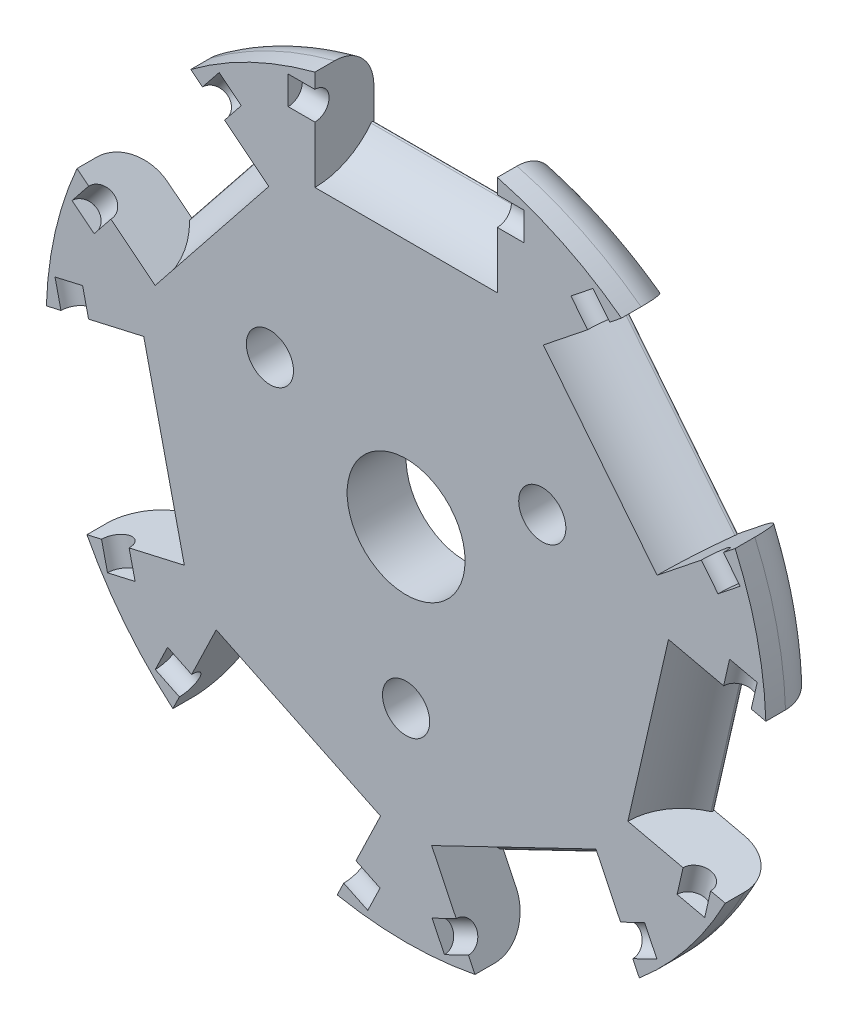
SolidWorks part; units mm, degrees
other "Markup1"
sketch "Sketch8" plane through (32.7336, 32.7336, 0) normal (0.5701, 0.1846, 0.8006) x (0.8043, 0.0736, -0.5897)
ref_plane "Front Plane" through (0, 0, 0) normal (0, 0, 1) x (1, 0, 0)
ref_plane "Top Plane" through (0, 0, 0) normal (0, 1, 0) x (1, 0, 0)
ref_plane "Right Plane" through (0, 0, 0) normal (1, 0, 0) x (0, 0, -1)
sketch "Sketch1" plane through (0, 0, 0) normal (0, 0, 1) x (1, 0, 0)
  circle A0 centre (0, 0) radius 29.0703
  dimension "D1" = 58.1406
extrude "Boss-Extrude2" add sketch "Sketch1" against normal blind 4.7625
fillet "Fillet1" radius 3.175 1 edges at (29.0703, 0, -4.7625)
sketch "Sketch2" plane through (0, 0, 0) normal (0, 0, 1) x (1, 0, 0)
  line L1 (-12.7, 29.0703) -> (12.7, 29.0703) construction
  line L2 (-7.366, 30.3403) -> (7.366, 30.3403)
  line L3 (-7.366, 30.3403) -> (-7.366, 19.9263)
  line L4 (-7.366, 19.9263) -> (7.366, 19.9263)
  line L5 (7.366, 30.3403) -> (7.366, 19.9263)
  line L6 (-7.366, 30.3403) -> (7.366, 19.9263) construction
  line L7 (-7.366, 19.9263) -> (7.366, 30.3403) construction
  line L35 (0, 0) -> (0, 29.0703) construction
  circle A1 centre (0, 0) radius 29.0703 construction
  point P10 (0, 25.1333)
  circle M7 centre (0, 0) radius 29.0703
  dimension "D1" = 14.732
  dimension "D2" = 10.414
  dimension "D3" = 1.27
  dimension "D4" = 25.4
extrude "Cut-Extrude2" cut sketch "Sketch2" against normal blind 12.7 contours L5 L3 L4 M7
pattern_circular "CirPattern1" count 7 over 360 about axis through (0, 0, 0) along (0, 0, 1) of "Cut-Extrude2"
ref_plane "Plane1" through (0, 0, 0) normal (1, 0, 0) x (0, 0, -1)
sketch "Sketch4" plane through (0, 0, 0) normal (1, 0, 0) x (0, 0, -1)
  line L0 (4.7625, 19.9263) -> (0, 19.9263) construction
  circle A0 centre (0, 25.7683) radius 1.143
  dimension "D1" = 2.286
  dimension "D2" = 5.842
extrude "Cut-Extrude4" cut sketch "Sketch4" against normal mid plane 19.05
pattern_circular "CirPattern2" count 7 over 360 about axis through (0, 0, 0) along (0, 0, 1) of "Cut-Extrude4"
sketch "Sketch5" plane through (0, 0, 0) normal (0, 0, 1) x (1, 0, 0)
  circle A0 centre (0, 0) radius 4.7625
  dimension "D1" = 9.525
sketch "Sketch6" plane through (0, 0, -4.7625) normal (0, 0, -1) x (-1, 0, 0)
  circle A1 centre (0, -12.7) radius 1.905
  circle A4 centre (-10.9985, 6.35) radius 1.905
  circle A5 centre (10.9985, 6.35) radius 1.905
  point P0 (0, -11.1125)
  point P12 (0, 0)
  dimension "D4" = 3.81
  dimension "D1" = 12.7
  dimension "D2" = 3
extrude "Cut-Extrude7" cut sketch "Sketch6" against normal through all
sketch "Sketch10" plane through (7.366, 0, 0) normal (-1, 0, 0) x (0, 0, 1)
  line L0 (-4.7625, 24.8256) -> (-4.7625, 19.9263) construction
  line L1 (-4.7625, 19.9263) -> (0, 19.9263)
  line L2 (-4.7625, 19.9263) -> (-4.7625, 22.6092)
  line L4 (0, 19.9263) -> (0, 20.0533)
  arc A0 (-4.7625, 22.6092) -> (0, 20.0533) centre (0, 25.7683) ccw
  dimension "D1" = 11.43
  dimension "D2" = 4.7625
extrude "Boss-Extrude4" add sketch "Sketch10" along normal up to next
fillet "Fillet2" radius 0.127 1 edges at (0, 22.6092, -4.7625)
pattern_circular "CirPattern5" count 7 over 360 about axis through (0, 0, 0) along (0, 0, 1) of "Boss-Extrude4", "Fillet2"
extrude "Cut-Extrude9" cut sketch "Sketch5" against normal up to next
